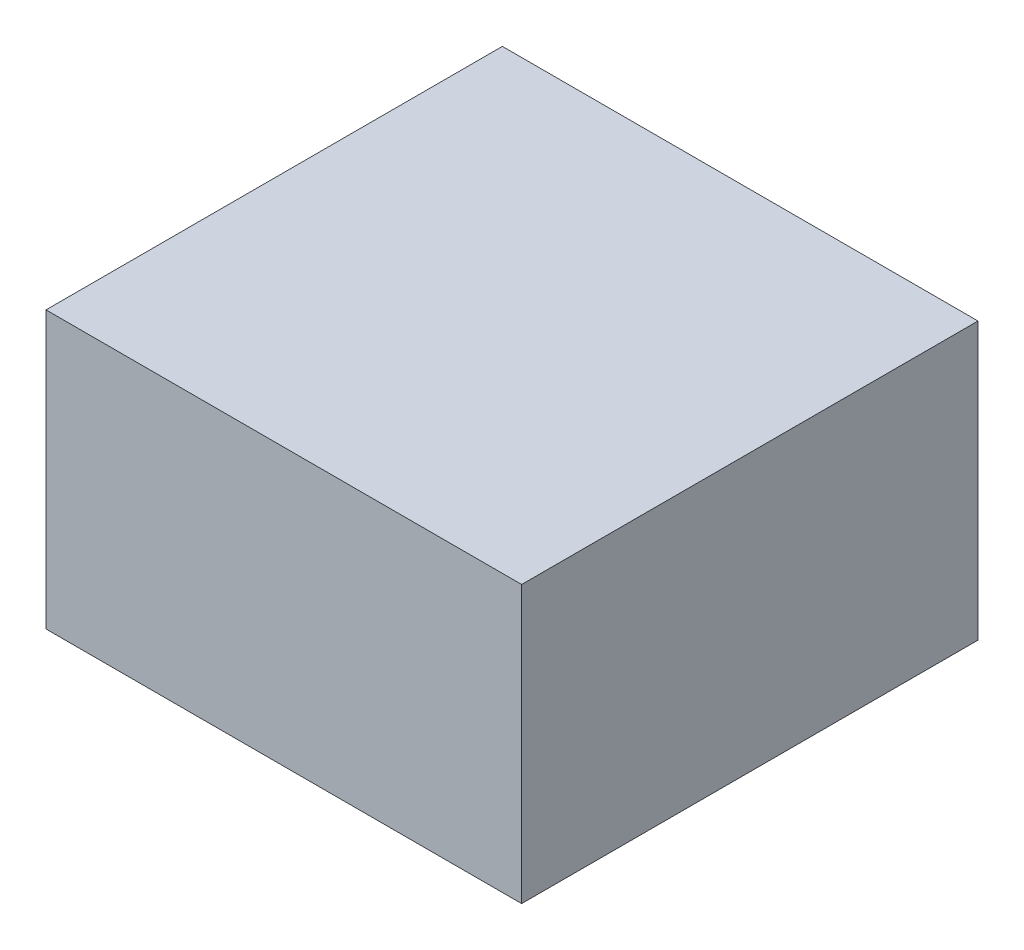
SolidWorks part; units mm, degrees
ref_plane "Front Plane" through (0, 0, 0) normal (0, 0, 1) x (1, 0, 0)
ref_plane "Top Plane" through (0, 0, 0) normal (0, 1, 0) x (1, 0, 0)
ref_plane "Right Plane" through (0, 0, 0) normal (1, 0, 0) x (0, 0, -1)
sketch "Sketch1" plane through (0, 0, 0) normal (0, 1, 0) x (1, 0, 0)
  line L1 (0, 0) -> (74, 0)
  line L2 (0, 0) -> (0, 71)
  line L3 (0, 71) -> (74, 71)
  line L4 (74, 0) -> (74, 71)
extrude "Boss-Extrude1" add sketch "Sketch1" along normal blind 43
